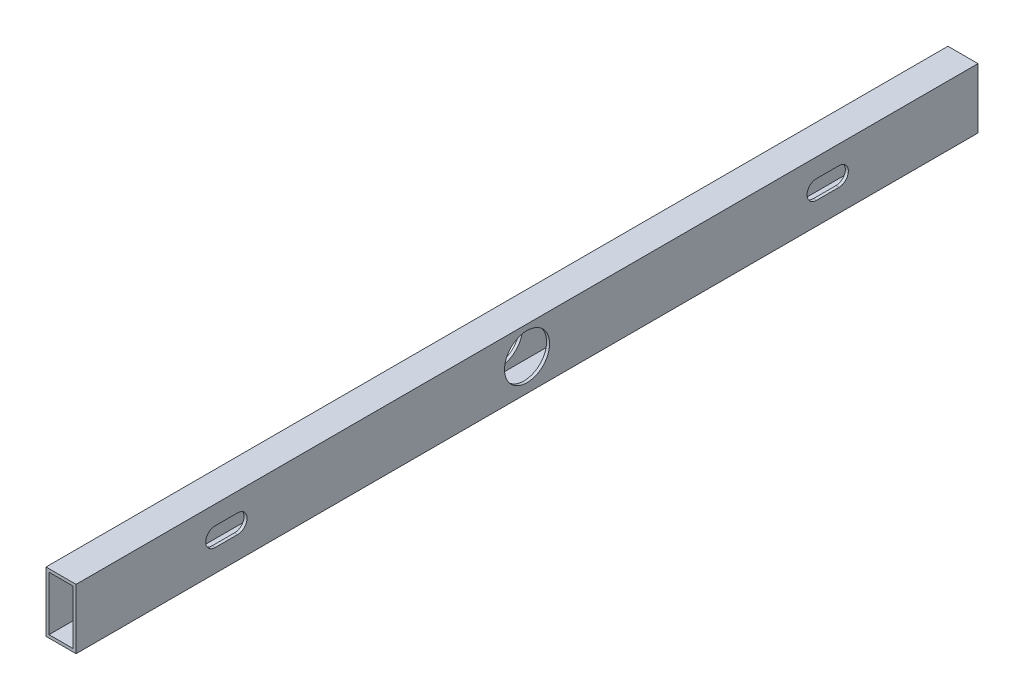
SolidWorks part; units mm, degrees
material "1060 Alloy"
ref_plane "Front Plane" through (0, 0, 0) normal (0, 0, 1) x (1, 0, 0)
ref_plane "Top Plane" through (0, 0, 0) normal (0, 1, 0) x (1, 0, 0)
ref_plane "Right Plane" through (0, 0, 0) normal (1, 0, 0) x (0, 0, -1)
sketch "Sketch1" plane through (0, 0, 0) normal (0, 0, 1) x (1, 0, 0)
  line L1 (-12.7, -25.4) -> (12.7, -25.4)
  line L2 (-12.7, -25.4) -> (-12.7, 25.4)
  line L3 (-12.7, 25.4) -> (12.7, 25.4)
  line L4 (12.7, -25.4) -> (12.7, 25.4)
  line L5 (-12.7, -25.4) -> (12.7, 25.4) construction
  line L6 (-12.7, 25.4) -> (12.7, -25.4) construction
  point P0 (0, 0)
  dimension "D1" = 25.4
  dimension "D2" = 50.8
extrude "Extrude-Thin1" add sketch "Sketch1" along normal mid plane 762 thin thin type one direction reverse wall 2.54
sketch "Sketch3" plane through (12.7, 0, 0) normal (1, 0, 0) x (0, 0, -1)
  line L0 (0, 25.4) -> (0, -25.4) construction
  line L6 (-381, 1.524) -> (381, 1.524) construction
  line L7 (-381, -25.4) -> (-381, 25.4) construction
  line L8 (381, -25.4) -> (381, 25.4) construction
  line L10 (244.475, 1.524) -> (263.525, 1.524) construction
  line L11 (244.475, 9.4615) -> (263.525, 9.4615)
  line L12 (244.475, -6.4135) -> (263.525, -6.4135)
  line L13 (-381, 25.4) -> (381, 25.4) construction
  line L14 (-381, -25.4) -> (381, -25.4) construction
  line L15 (-244.475, 1.524) -> (-263.525, 1.524) construction
  line L16 (-244.475, 9.4615) -> (-263.525, 9.4615)
  line L17 (-244.475, -6.4135) -> (-263.525, -6.4135)
  circle A0 centre (0, 1.524) radius 19.05
  arc A7 (244.475, 9.4615) -> (244.475, -6.4135) centre (244.475, 1.524) ccw
  arc A8 (263.525, -6.4135) -> (263.525, 9.4615) centre (263.525, 1.524) ccw
  arc A9 (-244.475, 9.4615) -> (-244.475, -6.4135) centre (-244.475, 1.524) cw
  arc A10 (-263.525, -6.4135) -> (-263.525, 9.4615) centre (-263.525, 1.524) cw
  point P4 (-254, 1.524)
  point P9 (254, 1.524)
  dimension "D2" = 38.1
  dimension "D1" = 23.876
  dimension "D3" = 127
  dimension "D4" = 19.05
  dimension "D5" = 15.875
extrude "Cut-Extrude1" cut sketch "Sketch3" against normal through all
